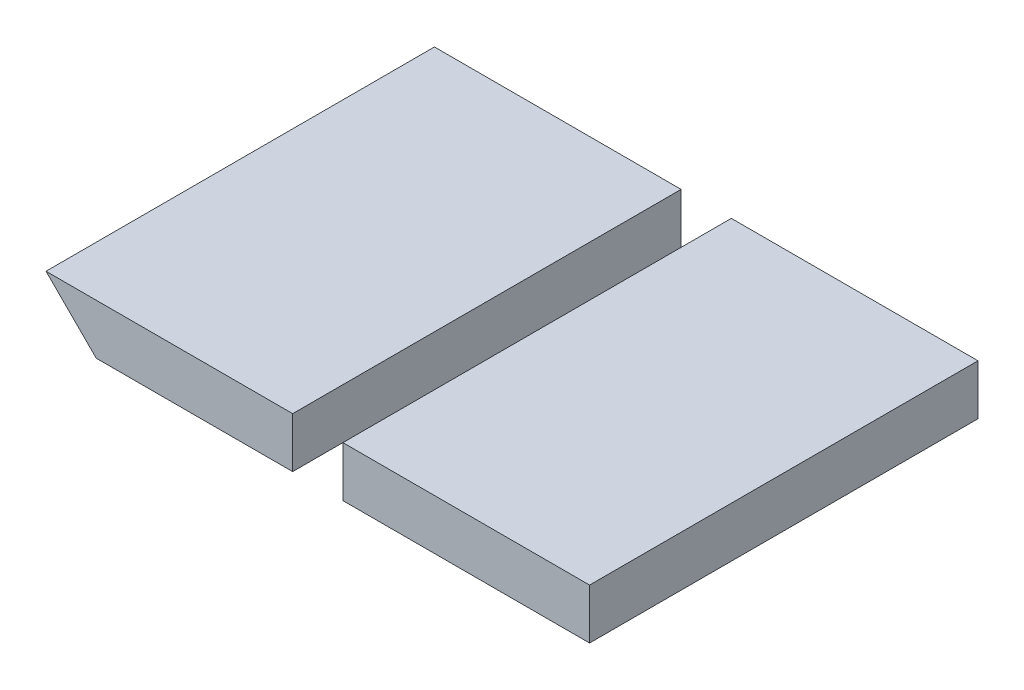
SolidWorks part; units mm, degrees
ref_plane "Plan de face" through (0, 0, 0) normal (0, 0, 1) x (1, 0, 0)
ref_plane "Plan de dessus" through (0, 0, 0) normal (0, 1, 0) x (1, 0, 0)
ref_plane "Plan de droite" through (0, 0, 0) normal (1, 0, 0) x (0, 0, -1)
sketch "Sketch1" plane through (0, 0, 0) normal (0, 0, 1) x (1, 0, 0)
  line L0 (-21.6361, 21.6361) -> (21.6361, 21.6361)
  line L1 (-19.05, -19.05) -> (19.05, -19.05)
  line L2 (-19.05, -19.05) -> (-19.05, 19.05)
  line L3 (-19.05, 19.05) -> (19.05, 19.05)
  line L4 (19.05, -19.05) -> (19.05, 19.05)
  line L5 (-19.05, -19.05) -> (19.05, 19.05) construction
  line L6 (-19.05, 19.05) -> (19.05, -19.05) construction
  line L7 (21.6361, -21.6361) -> (21.6361, 21.6361)
  line L8 (-21.6361, -21.6361) -> (21.6361, -21.6361)
  line L9 (-21.6361, -21.6361) -> (-21.6361, 21.6361)
  line L10 (-21.6361, 21.6361) -> (-19.05, 19.05)
  line L11 (-8.9361, 21.6361) -> (-8.9361, 19.05)
  line L12 (-8.9361, 19.05) -> (-6.35, 19.05)
  line L13 (-6.35, 19.05) -> (-6.35, 21.6361)
  line L14 (-6.35, 21.6361) -> (6.35, 21.6361)
  line L15 (6.35, 21.6361) -> (6.35, 19.05)
  line L16 (19.05, 19.05) -> (21.6361, 21.6361)
  line L17 (8.9361, 19.05) -> (8.9361, 21.6361)
  line L18 (-8.9361, 21.6361) -> (-6.35, 21.6361)
  line L19 (6.35, 21.6361) -> (8.9361, 21.6361)
  point P0 (0, 0)
  dimension "D1" = 38.1
  dimension "D3" = 12.7
  dimension "D4" = 12.7
  dimension "D5" = 12.7
  dimension "D2" = 2.5861
extrude "Boss-Extrude1" add sketch "Sketch1" along normal blind 20 contours L11 L0 L10 L3 | L15 L0 L13 L3
equation "\"D2@Sketch1\"=(0.25in - 0.007in - 1.0)/2"
